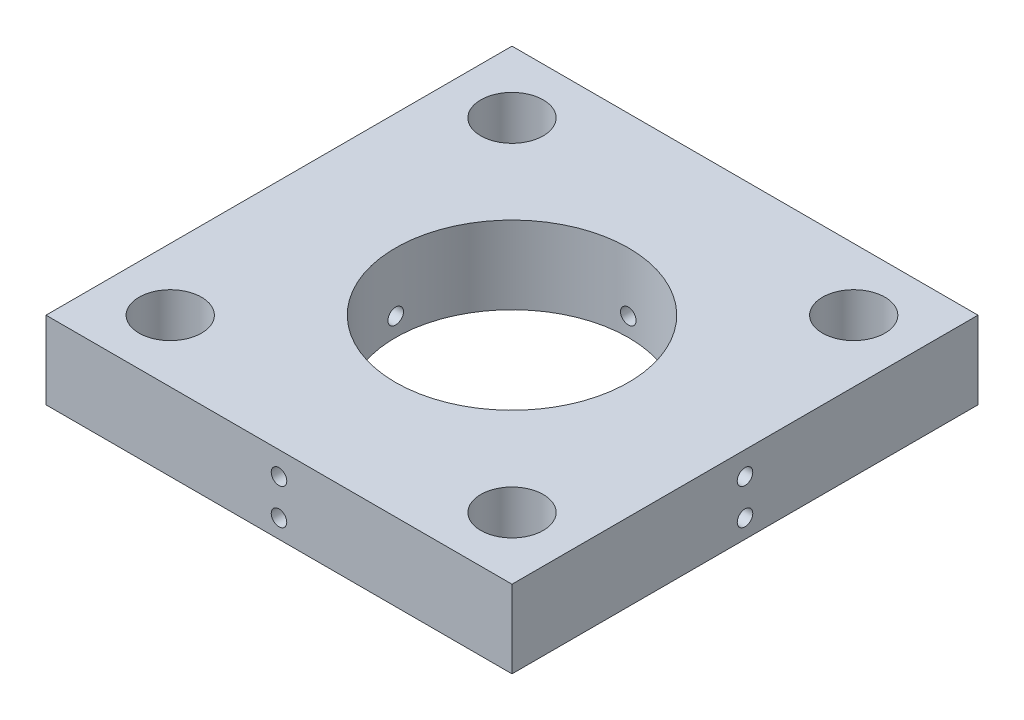
SolidWorks part; units mm, degrees
ref_plane "Front Plane" through (0, 0, 0) normal (0, 0, 1) x (1, 0, 0)
ref_plane "Top Plane" through (0, 0, 0) normal (0, 1, 0) x (1, 0, 0)
ref_plane "Right Plane" through (0, 0, 0) normal (1, 0, 0) x (0, 0, -1)
sketch "Sketch1" plane through (0, 0, 0) normal (0, 1, 0) x (1, 0, 0)
  line L1 (-19.05, 19.05) -> (19.05, 19.05)
  line L2 (-19.05, 19.05) -> (-19.05, -19.05)
  line L3 (-19.05, -19.05) -> (19.05, -19.05)
  line L4 (19.05, 19.05) -> (19.05, -19.05)
  line L5 (-19.05, 19.05) -> (19.05, -19.05) construction
  line L6 (-19.05, -19.05) -> (19.05, 19.05) construction
  point P0 (0, 0)
  dimension "D1" = 38.1
  dimension "D2" = 38.1
extrude "Boss-Extrude1" add sketch "Sketch1" along normal blind 6.35
sketch "Sketch2" plane through (0, 0, 0) normal (0, -1, 0) x (1, 0, 0)
  circle A0 centre (0, 0) radius 9.525
  dimension "D1" = 19.05
extrude "Cut-Extrude1" cut sketch "Sketch2" against normal through all
sketch "Sketch3" plane through (0, 0, 19.05) normal (0, 0, 1) x (1, 0, 0)
  line L0 (-19.05, 0) -> (19.05, 0) construction
  circle A0 centre (0, 1.524) radius 0.635
  dimension "D1" = 1.27
  dimension "D2" = 1.524
extrude "Cut-Extrude2" cut sketch "Sketch3" against normal through all
pattern_circular "CirPattern1" count 4 over 360 about axis through (0, 6.35, 0) along (0, -1, 0) of "Cut-Extrude2"
sketch "Sketch4" plane through (0, 0, 19.05) normal (0, 0, 1) x (1, 0, 0)
  line L0 (-19.05, 6.35) -> (19.05, 6.35) construction
  line L1 (19.05, 6.35) -> (19.05, 0) construction
  circle A0 centre (0, 4.445) radius 0.635
  point P2 (0, 6.35)
  dimension "D1" = 1.27
  dimension "D2" = 1.905
  dimension "D3" = 19.05
extrude "Cut-Extrude3" cut sketch "Sketch4" against normal blind 5.08
pattern_circular "CirPattern2" count 4 over 360 about axis through (0, 0, 0) along (0, 1, 0) of "Cut-Extrude3"
hole_wizard "Tap Drill for 1/4-20 Tap1" positions "Sketch6" profile "Sketch5" hole size "1/4-20" standard "ANSI Inch" end condition through all
sketch "Sketch6" plane through (0, 6.35, 0) normal (0, 1, 0) x (1, 0, 0)
  line L0 (-19.05, 19.05) -> (-19.05, -19.05) construction
  line L1 (19.05, 19.05) -> (-19.05, 19.05) construction
  line L2 (19.05, -19.05) -> (19.05, 19.05) construction
  line L3 (-19.05, -19.05) -> (19.05, -19.05) construction
  point P0 (-13.97, 13.97)
  point P7 (13.97, 13.97)
  point P12 (-13.97, -13.97)
  point P17 (13.97, -13.97)
  dimension "D1" = 5.08
  dimension "D2" = 5.08
  dimension "D3" = 5.08
  dimension "D4" = 5.08
  dimension "D5" = 5.08
  dimension "D6" = 5.08
  dimension "D7" = 5.08
  dimension "D8" = 5.08
sketch "Sketch5" plane through (-13.97, 6.35, -13.97) normal (1, 0, 0) x (0, 0, 1)
  line L0 (0, 0) -> (0, 6.35)
  line L1 (0, 6.35) -> (2.5527, 6.35)
  line L2 (2.5527, 6.35) -> (2.5527, 0)
  line L5 (2.5527, 0) -> (0, 0)
  line L11 (0, -6.35) -> (0, 107.95) construction
  dimension "Thru Hole Dia." = 5.1054
  dimension "Thru Hole Depth" = 6.35
